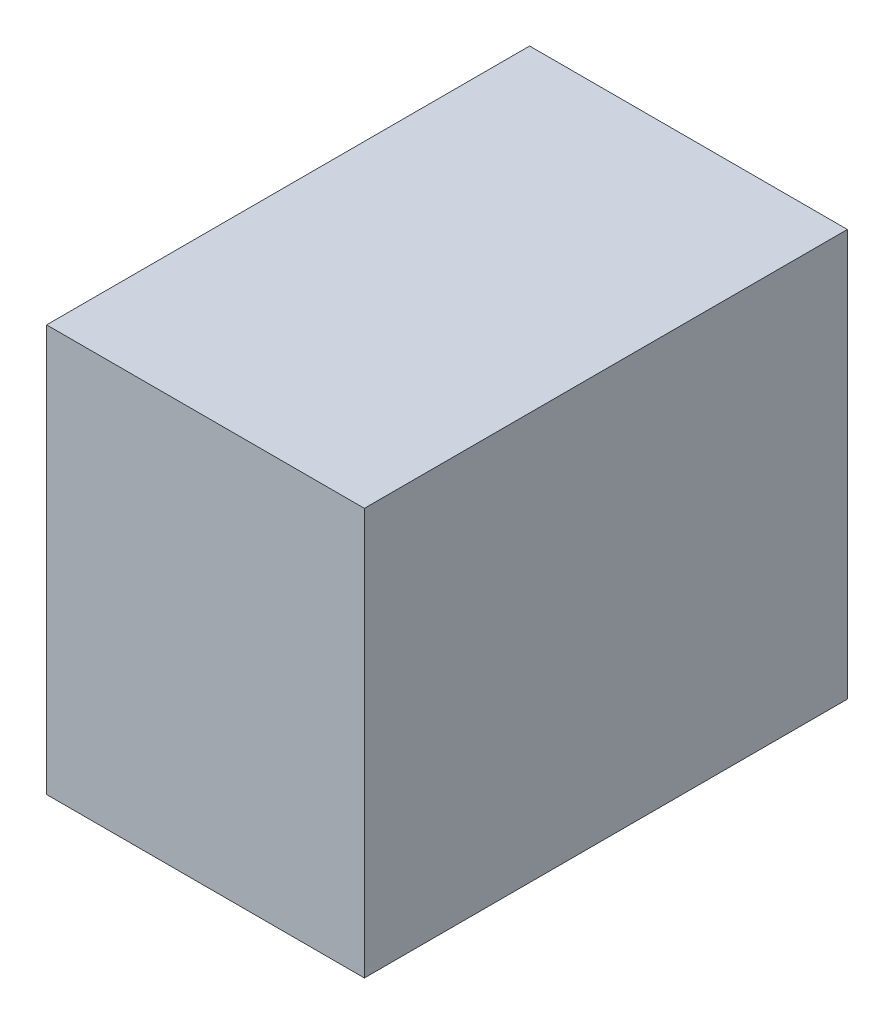
SolidWorks part; units mm, degrees
ref_plane "Front Plane" through (0, 0, 0) normal (0, 0, 1) x (1, 0, 0)
ref_plane "Top Plane" through (0, 0, 0) normal (0, 1, 0) x (1, 0, 0)
ref_plane "Right Plane" through (0, 0, 0) normal (1, 0, 0) x (0, 0, -1)
sketch "Sketch1" plane through (0, 0, 0) normal (0, 0, 1) x (1, 0, 0)
  line L1 (2.9, 28.1383) -> (2.9, -3.8617)
  line L6 (2.9, -3.8617) -> (27.9, -3.8617)
  line L8 (2.9, 28.1383) -> (27.9, 28.1383)
  line L9 (27.9, -3.8617) -> (27.9, 28.1383)
extrude "Boss-Extrude1" add sketch "Sketch1" along normal blind 38
